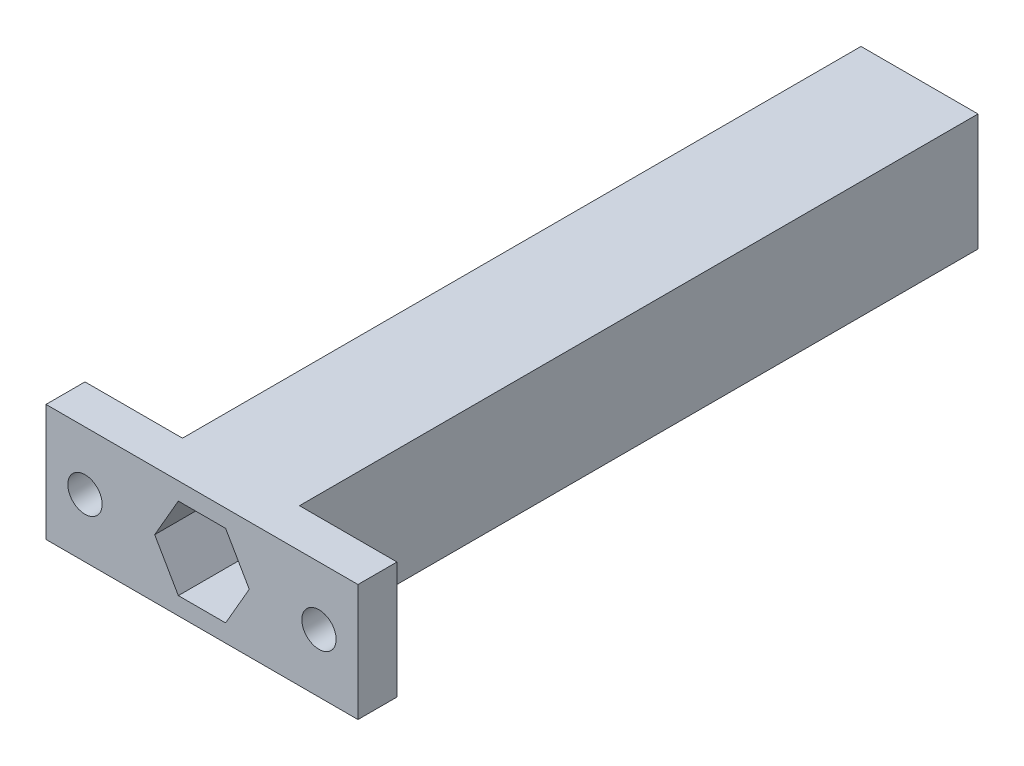
SolidWorks part; units mm, degrees
ref_plane "Front Plane" through (0, 0, 0) normal (0, 0, 1) x (1, 0, 0)
ref_plane "Top Plane" through (0, 0, 0) normal (0, 1, 0) x (1, 0, 0)
ref_plane "Right Plane" through (0, 0, 0) normal (1, 0, 0) x (0, 0, -1)
sketch "Sketch1" plane through (0, 0, 0) normal (0, 0, 1) x (1, 0, 0)
  line L1 (51, 33.5) -> (36, 33.5)
  line L2 (51, 33.5) -> (51, 18.5)
  line L3 (51, 18.5) -> (36, 18.5)
  line L4 (36, 33.5) -> (36, 18.5)
  line L5 (51, 33.5) -> (36, 18.5) construction
  line L6 (51, 18.5) -> (36, 33.5) construction
  circle A3 centre (43.5, 26) radius 3.2
  point P6 (0, 0)
  point P7 (0, 0)
  dimension "D2" = 15
  dimension "D3" = 15
  dimension "D1" = 6.4
extrude "Boss-Extrude1" add sketch "Sketch1" along normal blind 92
sketch "Sketch4" plane through (0, 0, 92) normal (0, 0, 1) x (1, 0, 0)
  line L0 (36, 18.5) -> (51, 18.5) construction
  line L1 (23.5, 33.5) -> (63.5, 33.5)
  line L2 (23.5, 33.5) -> (23.5, 18.5)
  line L3 (23.5, 18.5) -> (63.5, 18.5)
  line L4 (63.5, 33.5) -> (63.5, 18.5)
  line L5 (23.5, 33.5) -> (63.5, 18.5) construction
  line L6 (23.5, 18.5) -> (63.5, 33.5) construction
  circle A0 centre (58.5, 26) radius 2.2
  circle A1 centre (28.5, 26) radius 2.2
  point P0 (43.5, 26)
  dimension "D1" = 4.4
  dimension "D2" = 4.4
  dimension "D3" = 30
  dimension "D4" = 15
  dimension "D5" = 40
extrude "Boss-Extrude2" add sketch "Sketch4" against normal blind 5
sketch "Sketch3" plane through (0, 0, 92) normal (0, 0, 1) x (1, 0, 0)
  line L1 (40.4689, 20.75) -> (46.5311, 20.75)
  line L2 (46.5311, 20.75) -> (49.5622, 26)
  line L3 (49.5622, 26) -> (46.5311, 31.25)
  line L4 (46.5311, 31.25) -> (40.4689, 31.25)
  line L5 (40.4689, 31.25) -> (37.4378, 26)
  line L6 (37.4378, 26) -> (40.4689, 20.75)
  circle A0 centre (43.5, 26) radius 5.25 construction
  dimension "D1" = 10.5
extrude "Cut-Extrude1" cut sketch "Sketch3" against normal blind 75
